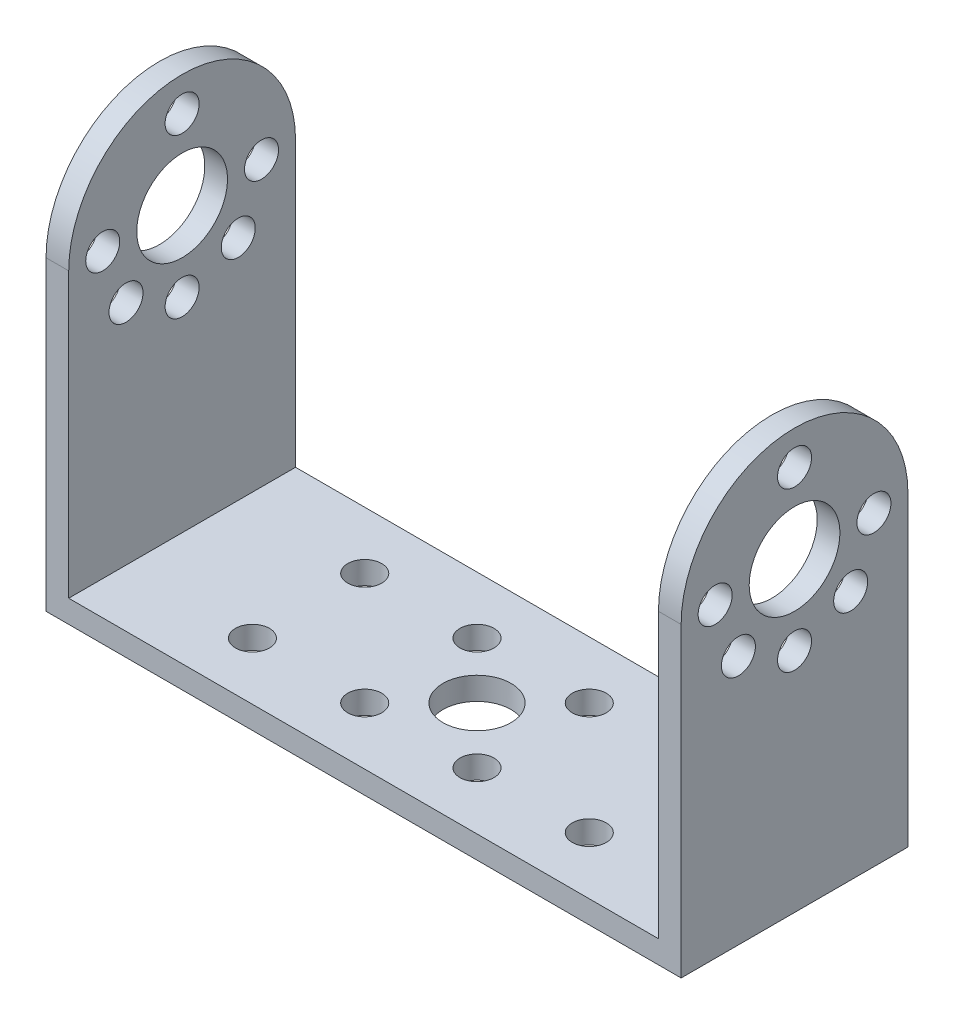
SolidWorks part; units mm, degrees
ref_plane "前视基准面" through (0, 0, 0) normal (0, 0, 1) x (1, 0, 0)
ref_plane "上视基准面" through (0, 0, 0) normal (0, 1, 0) x (1, 0, 0)
ref_plane "右视基准面" through (0, 0, 0) normal (1, 0, 0) x (0, 0, -1)
sketch "草图1" plane through (0, 0, 0) normal (0, 1, 0) x (1, 0, 0)
  line L1 (0, 0) -> (56, 0)
  line L2 (0, 0) -> (0, 20)
  line L3 (0, 20) -> (56, 20)
  line L4 (56, 0) -> (56, 20)
  dimension "D1" = 20
  dimension "D2" = 56
extrude "凸台-拉伸1" add sketch "草图1" along normal blind 2
sketch "草图2" plane through (0, 2, 0) normal (0, 1, 0) x (1, 0, 0)
  line L0 (28, 20) -> (28, 0) construction
  line L1 (56, 20) -> (0, 20) construction
  line L2 (0, 10) -> (56, 10) construction
  line L3 (0, 20) -> (0, 0) construction
  line L4 (56, 0) -> (56, 20) construction
  line L5 (28, 10) -> (35.7612, 2.2388) construction
  line L6 (23.0503, 14.9497) -> (23.0503, 5.0503) construction
  line L7 (18.1005, 10) -> (25.8617, 2.2388) construction
  circle A0 centre (28, 10) radius 3
  circle A1 centre (28, 10) radius 7 construction
  circle A2 centre (32.9497, 5.0503) radius 1.5
  circle A3 centre (23.0503, 5.0503) radius 1.5
  circle A4 centre (23.0503, 14.9497) radius 1.5
  circle A5 centre (32.9497, 14.9497) radius 1.5
  circle A6 centre (18.1005, 10) radius 7 construction
  circle A7 centre (13.1508, 14.9497) radius 1.5
  circle A8 centre (13.1508, 5.0503) radius 1.5
  circle A9 centre (42.8492, 5.0503) radius 1.5
  circle A10 centre (42.8492, 14.9497) radius 1.5
  point P26 (28, 10)
  dimension "D1" = 4
extrude "切除-拉伸1" cut sketch "草图2" against normal up to next
sketch "草图3" plane through (0, 0, 0) normal (-1, 0, 0) x (0, 0, 1)
  line L1 (-20, 2) -> (0, 2)
  line L2 (-20, 2) -> (-20, 27)
  line L4 (0, 2) -> (0, 27)
  arc A0 (0, 27) -> (-20, 27) centre (-10, 27) ccw
  dimension "D5" = 10
  dimension "D1" = 25
  dimension "D2" = 20
  dimension "D3" = 25
  dimension "D4" = 25
extrude "凸台-拉伸2" add sketch "草图3" against normal blind 2
sketch "草图4" plane through (0, 0, 0) normal (-1, 0, 0) x (0, 0, 1)
  circle A0 centre (-10, 27) radius 4
  circle A1 centre (-10, 27) radius 7 construction
  circle A2 centre (-10, 34) radius 1.5
  circle A3 centre (-5.0503, 31.9497) radius 1.5 [skipped]
  circle A4 centre (-3, 27) radius 1.5
  circle A5 centre (-5.0503, 22.0503) radius 1.5
  circle A6 centre (-10, 20) radius 1.5
  circle A7 centre (-14.9497, 22.0503) radius 1.5
  circle A8 centre (-17, 27) radius 1.5
  circle A9 centre (-14.9497, 31.9497) radius 1.5 [skipped]
  point P23 (-10, 27)
  dimension "D1" = 8
  dimension "D2" = 14
extrude "切除-拉伸2" cut sketch "草图4" against normal up to next
ref_plane "基准面1" through (28, 0, 0) normal (-1, 0, 0) x (0, 0, 1)
mirror "镜向1" about plane through (28, 0, 0) normal (-1, 0, 0) of "凸台-拉伸2", "切除-拉伸2"
